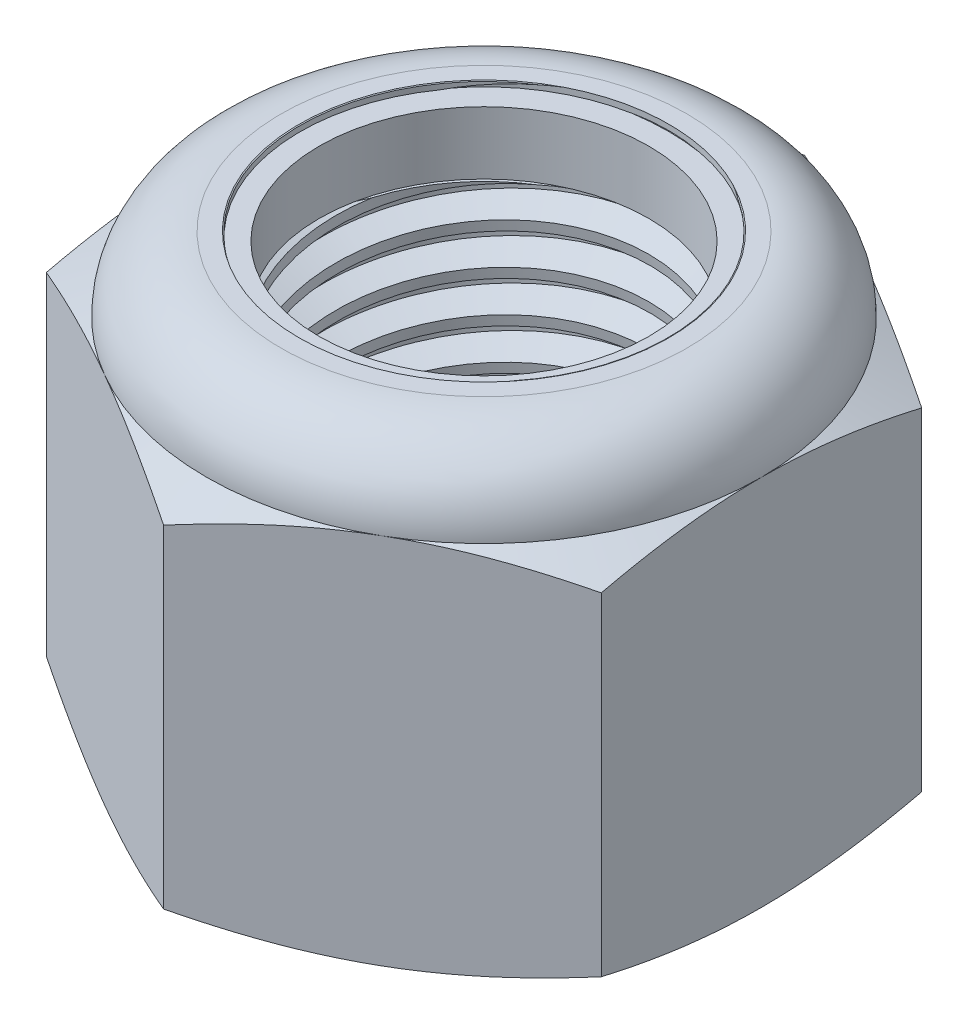
SolidWorks part; units mm, degrees
ref_plane "Front" through (0, 0, 0) normal (0, 0, 1) x (1, 0, 0)
ref_plane "Top" through (0, 0, 0) normal (0, 1, 0) x (1, 0, 0)
ref_plane "Right" through (0, 0, 0) normal (1, 0, 0) x (0, 0, -1)
sketch "Sketch1" plane through (0, 0, 0) normal (0, 1, 0) x (1, 0, 0)
  line L1 (0, 8.2489) -> (-7.1438, 4.1244)
  line L2 (-7.1438, 4.1244) -> (-7.1438, -4.1244)
  line L3 (-7.1438, -4.1244) -> (0, -8.2489)
  line L4 (0, -8.2489) -> (7.1437, -4.1244)
  line L5 (7.1437, -4.1244) -> (7.1437, 4.1244)
  line L6 (7.1437, 4.1244) -> (0, 8.2489)
  circle A0 centre (0, 0) radius 7.1438 construction
  dimension "Hex Flats" = 14.2875
extrude "Extrude1" add sketch "Sketch1" along normal blind 11.5094
sketch "Sketch2" plane through (0, 0, 0) normal (1, 0, 0) x (0, 0, -1)
  line L0 (-4.7625, 0) -> (-4.7625, 11.5094) construction
  line L1 (0, 0) -> (4.7625, 0)
  line L2 (0, 0) -> (0, 11.5094)
  line L3 (0, 11.5094) -> (4.7625, 11.5094)
  line L4 (4.7625, 0) -> (4.7625, 11.5094)
  line L5 (-4.1244, 11.5094) -> (4.1244, 11.5094) construction
  line L7 (0, -4.7625) -> (0, 0) construction
  dimension "Thread Dia" = 9.525
revolve "Revolve1" add sketch "Sketch2" angle 360 about L7
sketch "Sketch3" plane through (0, 0, 0) normal (1, 0, 0) x (0, 0, -1)
  line L0 (4.7625, 11.5094) -> (-4.7625, 11.5094) construction
  line L1 (-4.7625, 11.5094) -> (-4.7625, 10.451) construction
  line L2 (-4.7625, 10.451) -> (4.7625, 11.5094) construction
  line L3 (4.7625, 11.5094) -> (4.7771, 11.3779) construction
  line L4 (4.7771, 11.3779) -> (4.8794, 10.4575)
  line L5 (4.8794, 10.4575) -> (4.2735, 10.723)
  line L6 (4.2735, 10.723) -> (4.2443, 10.9859)
  line L7 (4.2443, 10.9859) -> (4.7771, 11.3779)
  line L8 (4.2589, 10.8544) -> (4.8282, 10.9177) construction
  line L9 (4.7625, 11.5094) -> (4.7625, 10.9104) construction
  line L10 (4.7625, 10.9104) -> (-4.7625, 9.8521) construction
  line L11 (-4.7625, 9.8521) -> (-4.7625, 10.451) construction
  line L12 (-0.1253, 11.5094) -> (0.1253, 9.2531) construction
  line L13 (-4.7625, 0) -> (-4.7625, 11.5094) construction
  line L14 (0, 11.5094) -> (4.7625, 11.5094) construction
  line L15 (4.7625, 0) -> (4.7625, 11.5094) construction
  point P13 (0, 10.3812)
  dimension "D1" = 0.1323
  dimension "D2" = 0.2646
  dimension "Thread Pitch" = 1.0583
  dimension "D4" = 60
  dimension "D5" = 1.0583
revolve "Cut-Revolve1" cut sketch "Sketch3" angle 360 about L12
pattern_linear "LPattern1" count 11 spacing 1.0583 along (0, -1, 0) count 2 spacing 1.0583 along (0, 1, 0) of "Cut-Revolve1"
sketch "Sketch4" plane through (0, 0, 0) normal (1, 0, 0) x (0, 0, -1)
  line L0 (0, 11.5094) -> (4.7625, 11.5094)
  line L1 (4.7625, 11.5094) -> (4.2443, 11.2677)
  line L2 (4.2443, 11.2677) -> (4.2443, 0.2416)
  line L3 (4.2443, 0.2416) -> (4.7625, 0)
  line L4 (4.7625, 0) -> (0, 0)
  line L5 (0, 0) -> (0, 11.5094)
  line L6 (4.7625, 0) -> (4.7625, 11.5094) construction
  line L7 (0, 11.5094) -> (4.7625, 11.5094) construction
  line L8 (0, 0) -> (4.7625, 0) construction
  line L9 (0, 0) -> (0, 11.5094) construction
  line L10 (0, 11.5094) -> (0, 12.0811) construction
  dimension "D1" = 25
revolve "Cut-Revolve2" cut sketch "Sketch4" angle 360 about L10
combine bodies "Combine1" operation type subtract main body 112 bodies to subtract 111
sketch "Sketch5" plane through (0, 0, 0) normal (1, 0, 0) x (0, 0, -1)
  line L0 (0, 0) -> (7.1438, 0)
  line L1 (7.1438, 0) -> (8.2489, 0.5153)
  line L2 (8.2489, 0.5153) -> (8.2489, 9.0758)
  line L3 (8.2489, 9.0758) -> (7.1438, 9.5911)
  line L4 (5.2255, 11.5094) -> (5.2255, 12.7794)
  line L5 (5.2255, 12.7794) -> (9.5189, 12.7794)
  line L6 (9.5189, 12.7794) -> (9.5189, -1.27)
  line L7 (9.5189, -1.27) -> (0, -1.27)
  line L8 (0, -1.27) -> (0, 0)
  line L9 (7.1438, 9.5911) -> (7.1438, 0) construction
  line L10 (0, 0) -> (4.7625, 0) construction
  line L13 (8.2489, 4.7956) -> (9.5189, 4.7956) construction
  line L14 (8.2489, 11.5094) -> (8.2489, 0) construction
  line L15 (0, 0) -> (0, 12.7794) construction
  line L20 (0, 12.7794) -> (5.2255, 12.7794) construction
  line L22 (0, 11.5094) -> (4.7625, 11.5094) construction
  arc A0 (7.1438, 9.5911) -> (5.2255, 11.5094) centre (5.2255, 9.5911) ccw
  dimension "D1" = 25
  dimension "D2" = 1.27
  dimension "D3" = 11.5094
  dimension "D4" = 1.9182
revolve "Cut-Revolve3" cut sketch "Sketch5" angle 360 about L15
sketch "Sketch6" plane through (0, 0, 0) normal (1, 0, 0) x (0, 0, -1)
  line L0 (0, 9.5911) -> (6.9914, 9.5911)
  line L1 (5.2255, 11.357) -> (4.7349, 11.357)
  line L2 (0, 12.7794) -> (0, 9.5911)
  line L3 (4.7349, 12.7794) -> (0, 12.7794)
  line L4 (0, 12.7794) -> (5.2255, 12.7794) construction
  line L5 (0, 0) -> (0, 12.7794) construction
  line L6 (0, 12.7794) -> (0, 44.323) construction
  line L7 (4.7349, 11.357) -> (4.7349, 12.7794)
  line L8 (5.2255, 11.5094) -> (5.2255, 11.357) construction
  line L9 (4.7349, 11.357) -> (4.2443, 11.357) construction
  line L10 (4.2443, 11.357) -> (4.2443, 11.2677) construction
  arc A0 (6.9914, 9.5911) -> (5.2255, 11.357) centre (5.2255, 9.5911) ccw
  arc A1 (7.1438, 9.5911) -> (5.2255, 11.5094) centre (5.2255, 9.5911) ccw construction
  dimension "D1" = 0.1524
revolve "Cut-Revolve4" cut sketch "Sketch6" angle 360 about L6
sketch "Sketch7" plane through (0, 0, 0) normal (1, 0, 0) x (0, 0, -1)
  line L0 (4.2443, 9.6673) -> (6.9134, 9.6673)
  line L1 (5.2255, 11.2808) -> (4.2443, 11.2808)
  line L2 (4.2443, 11.2808) -> (4.2443, 9.6673)
  line L3 (4.2443, 9.6673) -> (0, 9.6673) construction
  line L4 (0, 9.6673) -> (0, 11.2808) construction
  line L5 (0, 11.2808) -> (4.2443, 11.2808) construction
  line L6 (4.2443, 9.6673) -> (4.2443, 9.5911) construction
  line L7 (0, 9.5911) -> (6.9914, 9.5911) construction
  line L8 (5.2255, 11.2808) -> (5.2255, 11.357) construction
  arc A0 (6.9134, 9.6673) -> (5.2255, 11.2808) centre (5.2255, 9.5911) ccw
  arc A2 (6.9914, 9.5911) -> (5.2255, 11.357) centre (5.2255, 9.5911) ccw construction
  dimension "D1" = 0.0762
revolve "Revolve2" add sketch "Sketch7" angle 360 about L4
equation "\"D1@Sketch3\"=\"Thread Pitch@Sketch3\"/8"
equation "\"D2@Sketch3\"=\"Thread Pitch@Sketch3\"/4"
equation "\"D5@Sketch3\"=\"Thread Pitch@Sketch3\""
equation "\"D4@LPattern1\"=\"Thread Pitch@Sketch3\""
equation "\"D3@LPattern1\"=\"Thread Pitch@Sketch3\""
equation "\"D1@LPattern1\"=\"Height@Extrude1\"/\"Thread Pitch@Sketch3\""
equation "\"D4@Sketch5\"=\"Height@Extrude1\"/6"
